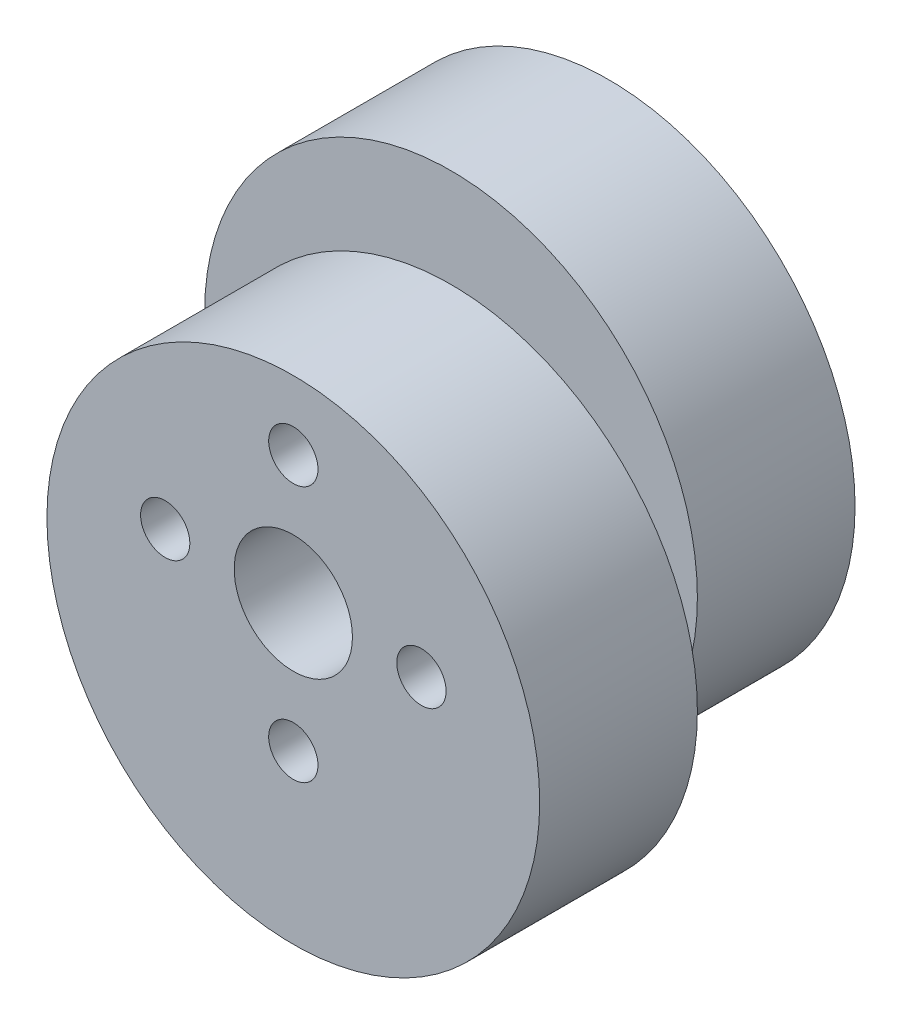
SolidWorks part; units mm, degrees
material "5052-H34"
ref_plane "正面" through (0, 0, 0) normal (0, 0, 1) x (1, 0, 0)
ref_plane "平面" through (0, 0, 0) normal (0, 1, 0) x (1, 0, 0)
ref_plane "右側面" through (0, 0, 0) normal (1, 0, 0) x (0, 0, -1)
sketch "ｽｹｯﾁ1" plane through (0, 0, 0) normal (0, 0, 1) x (1, 0, 0)
  line L0 (0, -12.5) -> (0, 12.5) construction
  circle A0 centre (0, 0) radius 12.5
  circle A1 centre (0, 2.5) radius 6.5 construction
  circle A2 centre (0, -4) radius 1.25
  circle A3 centre (-6.5, 2.5) radius 1.25
  circle A4 centre (0, 9) radius 1.25
  circle A5 centre (6.5, 2.5) radius 1.25
  circle A12 centre (0, 2.5) radius 3
  point P18 (0, 2.5)
  dimension "D1" = 25
  dimension "D2" = 13
  dimension "D3" = 2.5
  dimension "D6" = 6
  dimension "D5" = 2.5
  dimension "D4" = 4
extrude "ﾎﾞｽ - 押し出し3" add sketch "ｽｹｯﾁ1" along normal blind 8
sketch "ｽｹｯﾁ4" plane through (0, 0, 0) normal (0, 0, -1) x (-1, 0, 0)
  line L0 (0, 0) -> (0, 27.2172) construction
  circle A0 centre (0, 5) radius 12.5
  circle A1 centre (0, 9) radius 1.25 construction
  circle A2 centre (6.5, 2.5) radius 1.25 construction
  circle A3 centre (0, -4) radius 1.25 construction
  circle A4 centre (-6.5, 2.5) radius 1.25 construction
  circle A5 centre (0, 9) radius 1.25
  circle A6 centre (6.5, 2.5) radius 1.25
  circle A7 centre (0, -4) radius 1.25
  circle A8 centre (-6.5, 2.5) radius 1.25
  circle A9 centre (0, 0) radius 12.5 construction
  circle A11 centre (0, 2.5) radius 3 construction
  circle A13 centre (0, 2.5) radius 3
  point P5 (0, -6.566)
  point P18 (0, 5.9243)
  point P21 (0, 0)
  point P22 (0, 4.68)
  dimension "D1" = 2.5
extrude "ﾎﾞｽ - 押し出し4" add sketch "ｽｹｯﾁ4" along normal blind 8 separate body
